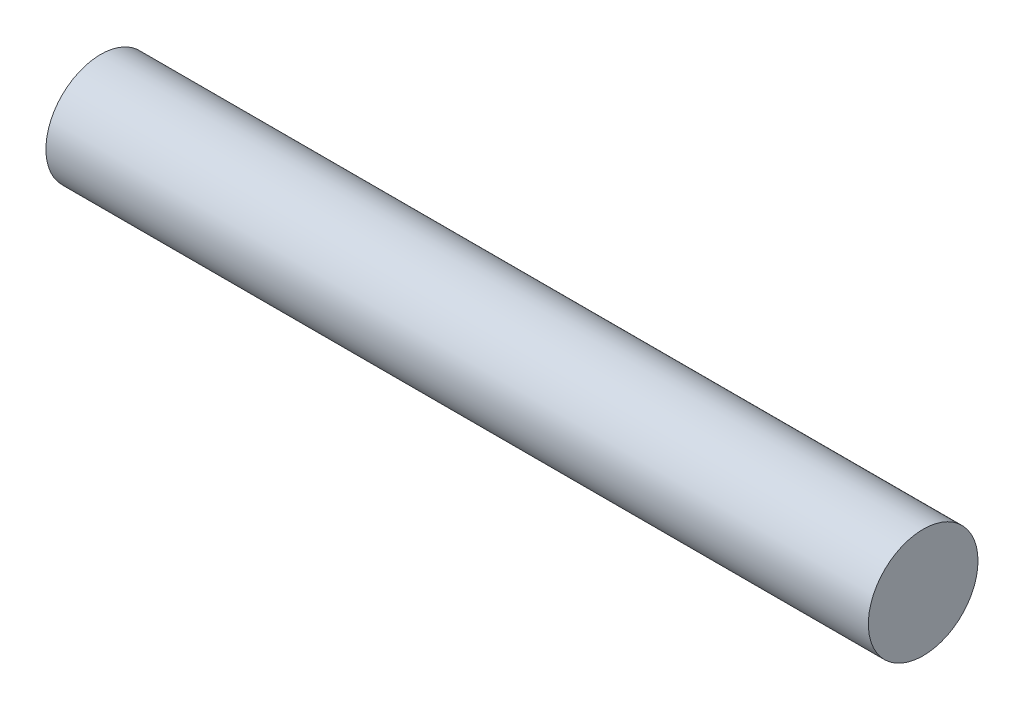
SolidWorks part; units mm, degrees
ref_plane "Plano frontal" through (0, 0, 0) normal (0, 0, 1) x (1, 0, 0)
ref_plane "Plano superior" through (0, 0, 0) normal (0, 1, 0) x (1, 0, 0)
ref_plane "Plano direito" through (0, 0, 0) normal (1, 0, 0) x (0, 0, -1)
sketch "Esboço1" plane through (0, 0, 0) normal (1, 0, 0) x (0, 0, -1)
  circle A0 centre (0, 0) radius 2
  dimension "D1" = 4
extrude "Ressalto-extrusão1" add sketch "Esboço1" along normal blind 30
